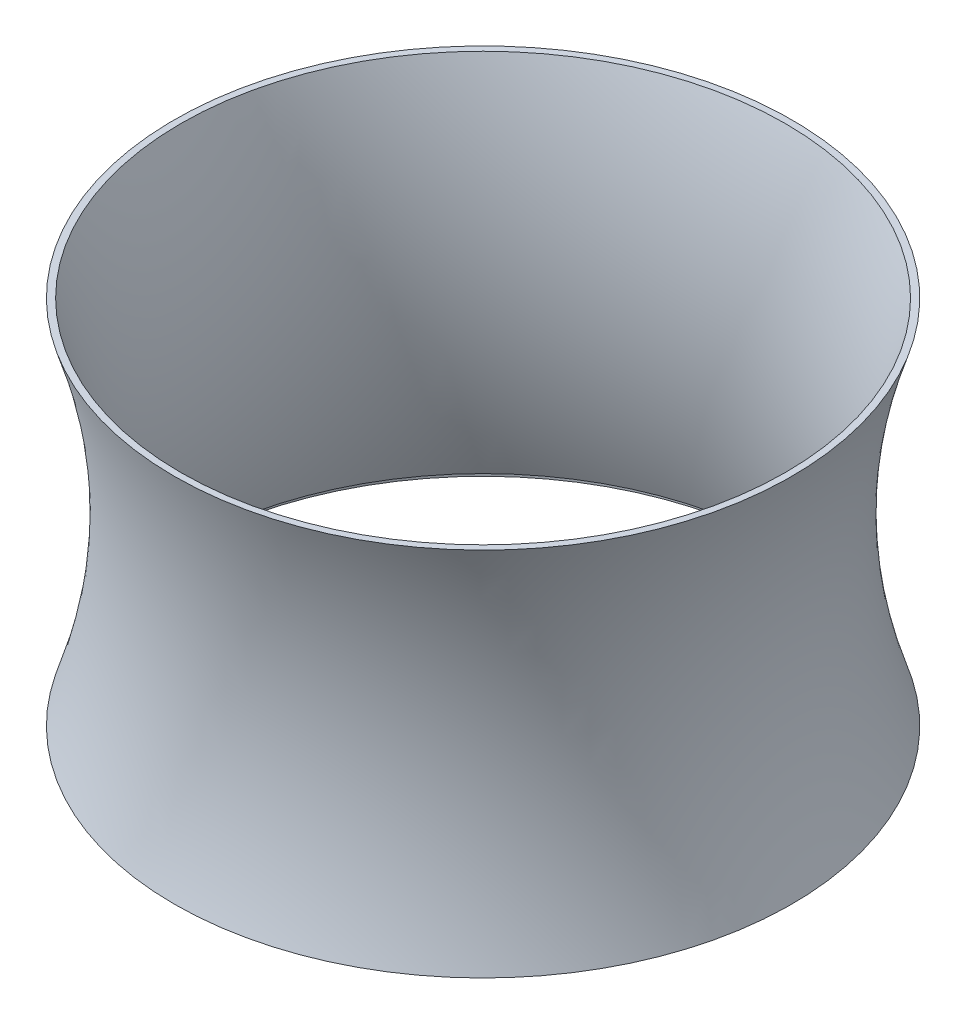
SolidWorks part; units mm, degrees
ref_plane "前视基准面" through (0, 0, 0) normal (0, 0, 1) x (1, 0, 0)
ref_plane "上视基准面" through (0, 0, 0) normal (0, 1, 0) x (1, 0, 0)
ref_plane "右视基准面" through (0, 0, 0) normal (1, 0, 0) x (0, 0, -1)
sketch "草图1" plane through (0, 0, 0) normal (0, 0, 1) x (1, 0, 0)
  line L0 (0, 30) -> (0, -30)
  line L1 (0, 30) -> (-50, 30)
  line L2 (0, -30) -> (-50, -30)
  spline S0 degree 2 poles (-50, 30) (-40, 0) (-50, -30) knots 0 0 0 1 1 1
  dimension "D1" = 60
  dimension "D2" = 50
revolve "旋转1" add sketch "草图1" angle 360 about L0
shell "抽壳1" thickness 1
sketch "草图2" plane through (0, -30, 0) normal (0, -1, 0) x (1, 0, 0)
  circle A0 centre (0, 0) radius 49.5
  dimension "D1" = 99
extrude "切除-拉伸1" cut sketch "草图2" against normal blind 1
